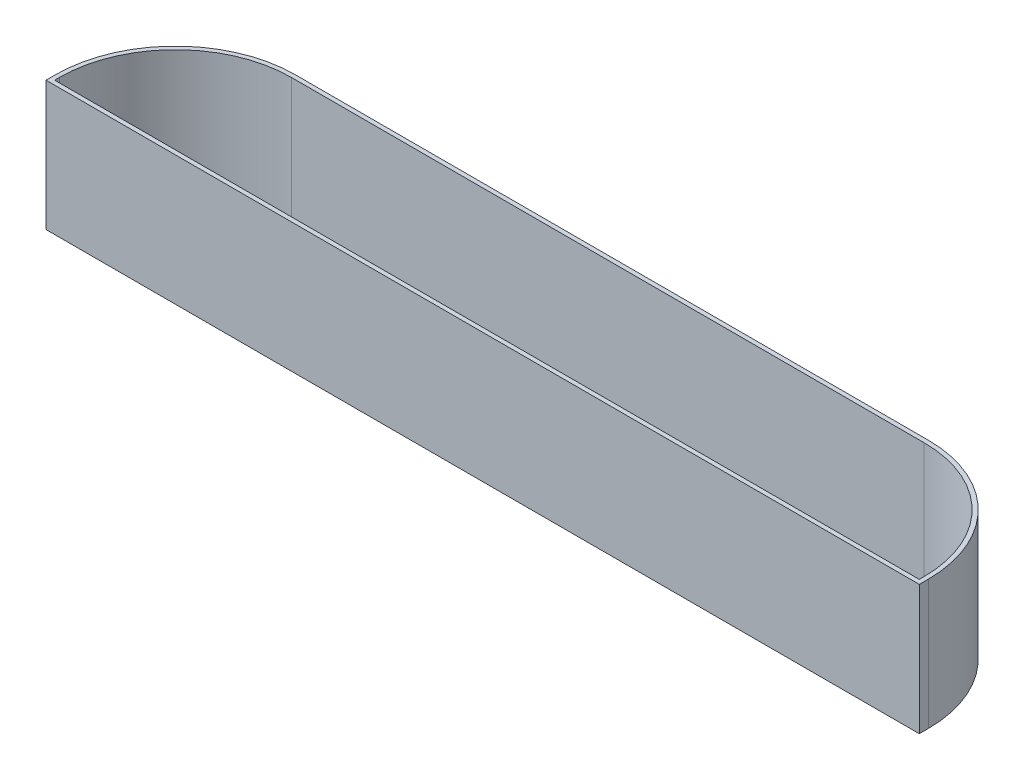
SolidWorks part; units mm, degrees
ref_plane "Front Plane" through (0, 0, 0) normal (0, 0, 1) x (1, 0, 0)
ref_plane "Top Plane" through (0, 0, 0) normal (0, 1, 0) x (1, 0, 0)
ref_plane "Right Plane" through (0, 0, 0) normal (1, 0, 0) x (0, 0, -1)
sketch "Sketch1" plane through (0, 0, 0) normal (0, 1, 0) x (1, 0, 0)
  line L0 (-257.175, 0) -> (257.175, 0)
  line L1 (-257.175, 0) -> (-257.175, 5.4)
  line L2 (-186.375, 76.2) -> (186.375, 76.2)
  line L3 (257.175, 5.4) -> (257.175, 0)
  line L4 (254.635, 5.4) -> (254.635, 2.54)
  line L5 (-254.635, 2.54) -> (254.635, 2.54)
  line L6 (-254.635, 2.54) -> (-254.635, 5.4)
  line L7 (-186.375, 73.66) -> (186.375, 73.66)
  arc A0 (186.375, 76.2) -> (257.175, 5.4) centre (186.375, 5.4) cw
  arc A1 (-257.175, 5.4) -> (-186.375, 76.2) centre (-186.375, 5.4) cw
  arc A2 (-254.635, 5.4) -> (-186.375, 73.66) centre (-186.375, 5.4) cw
  arc A3 (186.375, 73.66) -> (254.635, 5.4) centre (186.375, 5.4) cw
  point P3 (0, 0)
  point P10 (-257.175, 76.2)
  dimension "D3" = 70.8
  dimension "D1" = 514.35
  dimension "D2" = 76.2
  dimension "D4" = 2.54
extrude "Boss-Extrude1" add sketch "Sketch1" along normal blind 76.2
sketch "Sketch3" plane through (0, 0, -76.2) normal (0, 0, -1) x (-1, 0, 0)
  line L0 (0, 73.2) -> (-4, 67.2)
  line L1 (-4, 67.2) -> (0, 61.2)
  line L2 (0, 61.2) -> (4, 67.2)
  line L3 (4, 67.2) -> (0, 73.2)
  line L4 (-186.375, 76.2) -> (186.375, 76.2) construction
  line L5 (-5.8028, 64.4958) -> (-9.8028, 58.4958)
  line L6 (-9.8028, 58.4958) -> (-5.8028, 52.4958)
  line L7 (-5.8028, 52.4958) -> (-1.8028, 58.4958)
  line L8 (-1.8028, 58.4958) -> (-5.8028, 64.4958)
  point P2 (0, 0)
  point P5 (0, 0)
  point P6 (-158.7355, 45.5838)
  point P7 (0, 0)
  point P8 (0, 0)
  point P16 (-8.0569, 50.7787)
  point P17 (-2, 64.2)
  point P18 (-5.4301, 63.9368)
  dimension "D1" = 12
  dimension "D2" = 8
  dimension "D3" = 3
  dimension "D4" = 8
  dimension "D5" = 3
